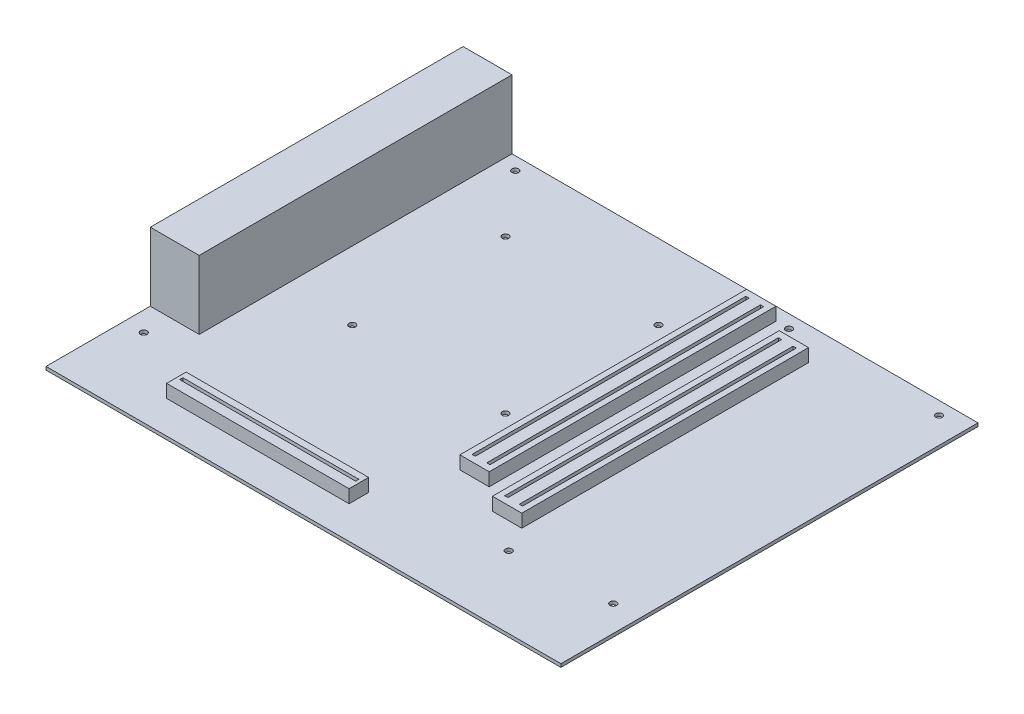
SolidWorks part; units mm, degrees
ref_plane "Front Plane" through (0, 0, 0) normal (0, 0, 1) x (1, 0, 0)
ref_plane "Top Plane" through (0, 0, 0) normal (0, 1, 0) x (1, 0, 0)
ref_plane "Right Plane" through (0, 0, 0) normal (1, 0, 0) x (0, 0, -1)
sketch "Sketch1" plane through (0, 0, 0) normal (0, 1, 0) x (1, 0, 0)
  line L0 (0, 0) -> (250.825, 0)
  line L1 (250.825, 0) -> (250.825, 203.2)
  line L2 (250.825, 203.2) -> (0, 203.2)
  line L3 (0, 203.2) -> (0, 0)
  circle A0 centre (31.75, 196.85) radius 1.5875
  circle A1 centre (165.1, 196.85) radius 1.5875
  circle A2 centre (238.252, 196.85) radius 1.5875
  circle A3 centre (238.252, 38.1) radius 1.5875
  circle A4 centre (190.5, 34.925) radius 1.5875
  circle A5 centre (9.525, 38.1) radius 1.5875
  circle A6 centre (57.15, 166.6875) radius 1.5875
  circle A7 centre (131.7625, 166.6875) radius 1.5875
  circle A8 centre (131.7625, 92.075) radius 1.5875
  circle A9 centre (57.15, 92.075) radius 1.5875
  dimension "D6" = 3.175
  dimension "D1" = 250.825
  dimension "D2" = 203.2
  dimension "D3" = 31.75
  dimension "D4" = 165.1
  dimension "D5" = 238.252
  dimension "D7" = 6.35
  dimension "D8" = 38.1
  dimension "D9" = 60.325
  dimension "D10" = 34.925
  dimension "D11" = 9.525
  dimension "D12" = 74.6125
  dimension "D13" = 74.6125
  dimension "D14" = 36.5125
  dimension "D15" = 57.15
extrude "Boss-Extrude1" add sketch "Sketch1" along normal blind 1.5875
sketch "Sketch2" plane through (0, 1.5875, 0) normal (0, 1, 0) x (1, 0, 0)
  line L0 (144.4625, 196.85) -> (144.4625, 57.15)
  line L1 (144.4625, 57.15) -> (158.75, 57.15)
  line L2 (158.75, 57.15) -> (158.75, 196.85)
  line L3 (158.75, 196.85) -> (144.4625, 196.85)
  line L4 (250.825, 203.2) -> (0, 203.2) construction
  line L5 (172.6406, 184.15) -> (174.2281, 184.15)
  line L6 (169.8625, 187.325) -> (184.15, 187.325)
  line L7 (169.8625, 187.325) -> (169.8625, 47.625)
  line L8 (169.8625, 47.625) -> (184.15, 47.625)
  line L9 (184.15, 187.325) -> (184.15, 47.625)
  line L10 (147.2406, 193.675) -> (148.8281, 193.675)
  line L11 (147.2406, 193.675) -> (147.2406, 60.325)
  line L12 (147.2406, 60.325) -> (148.8281, 60.325)
  line L13 (148.8281, 193.675) -> (148.8281, 60.325)
  line L14 (154.3844, 193.675) -> (155.9719, 193.675)
  line L15 (154.3844, 193.675) -> (154.3844, 60.325)
  line L16 (154.3844, 60.325) -> (155.9719, 60.325)
  line L17 (155.9719, 193.675) -> (155.9719, 60.325)
  line L18 (172.6406, 184.15) -> (172.6406, 50.8)
  line L19 (172.6406, 50.8) -> (174.2281, 50.8)
  line L20 (174.2281, 184.15) -> (174.2281, 50.8)
  line L21 (179.7844, 184.15) -> (181.3719, 184.15)
  line L22 (179.7844, 184.15) -> (179.7844, 50.8)
  line L23 (179.7844, 50.8) -> (181.3719, 50.8)
  line L24 (181.3719, 184.15) -> (181.3719, 50.8)
  line L25 (0, 203.2) -> (0, 0) construction
  line L26 (42.8625, 25.4) -> (131.7625, 25.4)
  line L27 (42.8625, 25.4) -> (42.8625, 15.875)
  line L28 (42.8625, 15.875) -> (131.7625, 15.875)
  line L29 (131.7625, 25.4) -> (131.7625, 15.875)
  line L30 (0, 0) -> (250.825, 0) construction
  line L32 (44.45, 22.225) -> (130.175, 22.225)
  line L33 (44.45, 22.225) -> (44.45, 20.6375)
  line L34 (44.45, 20.6375) -> (130.175, 20.6375)
  line L35 (130.175, 22.225) -> (130.175, 20.6375)
  point P27 (147.2406, 127)
  point P28 (144.4625, 127)
  point P29 (172.6406, 117.475)
  point P30 (169.8625, 117.475)
  point P31 (148.0344, 193.675)
  point P32 (155.1781, 193.675)
  point P33 (173.4344, 184.15)
  point P34 (180.5781, 184.15)
  dimension "D1" = 144.4625
  dimension "D3" = 6.35
  dimension "D4" = 139.7
  dimension "D5" = 139.7
  dimension "D6" = 14.2875
  dimension "D7" = 15.875
  dimension "D8" = 169.8625
  dimension "D2" = 14.2875
  dimension "D9" = 1.5875
  dimension "D10" = 133.35
  dimension "D11" = 3.5719
  dimension "D12" = 3.5719
  dimension "D13" = 3.5719
  dimension "D14" = 3.5719
  dimension "D15" = 42.8625
  dimension "D16" = 88.9
  dimension "D17" = 9.525
  dimension "D18" = 25.4
  dimension "D19" = 3.175
  dimension "D20" = 1.5875
  dimension "D21" = 1.5875
  dimension "D22" = 1.5875
extrude "Boss-Extrude2" add sketch "Sketch2" along normal blind 6.35
sketch "Sketch3" plane through (0, 1.5875, 0) normal (0, 1, 0) x (1, 0, 0)
  line L1 (0, 203.2) -> (23.8212, 203.2)
  line L2 (0, 203.2) -> (0, 50.8)
  line L3 (0, 50.8) -> (23.8212, 50.8)
  line L4 (23.8212, 203.2) -> (23.8212, 50.8)
  dimension "D1" = 152.4
extrude "Boss-Extrude3" add sketch "Sketch3" along normal blind 33.3375
equation "\"D11@Sketch2\"=\"D2@Sketch2\"/4"
equation "\"D12@Sketch2\"=\"D11@Sketch2\""
equation "\"D13@Sketch2\"=\"D11@Sketch2\""
equation "\"D14@Sketch2\"=\"D11@Sketch2\""
